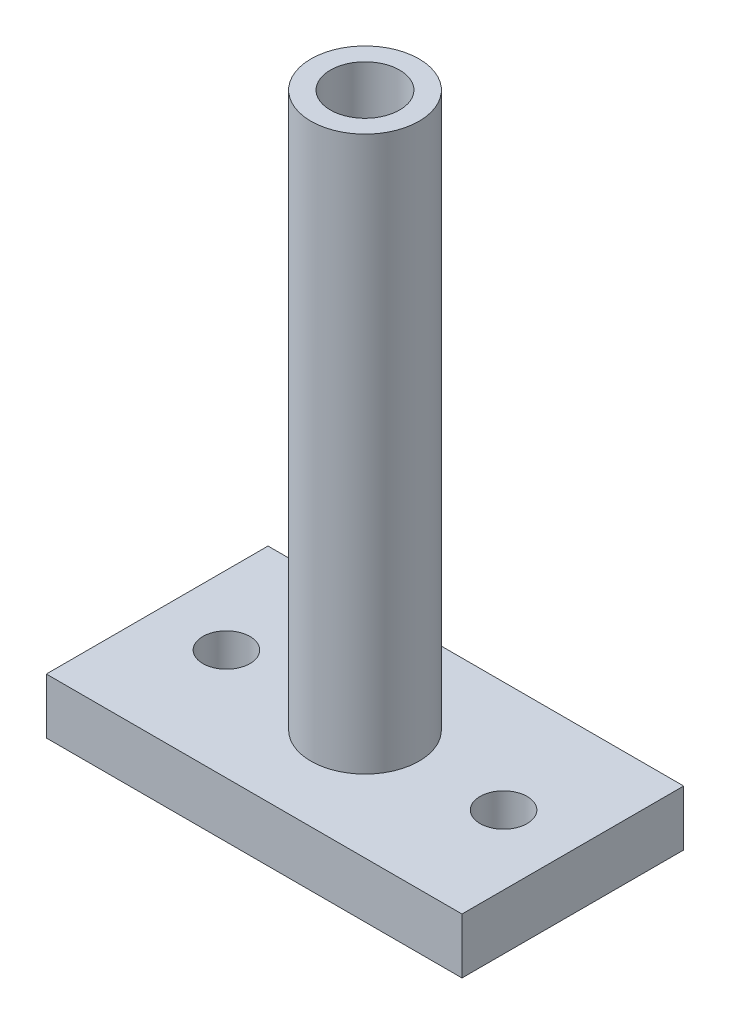
SolidWorks part; units mm, degrees
ref_plane "前视基准面" through (0, 0, 0) normal (0, 0, 1) x (1, 0, 0)
ref_plane "上视基准面" through (0, 0, 0) normal (0, 1, 0) x (1, 0, 0)
ref_plane "右视基准面" through (0, 0, 0) normal (1, 0, 0) x (0, 0, -1)
other "Configuration Table"
sketch "草图1" plane through (0, 0, 0) normal (0, 1, 0) x (1, 0, 0)
  line L0 (7.5, 0) -> (7.5, 8) construction
  line L1 (0, 0) -> (15, 0)
  line L2 (0, 0) -> (0, 8)
  line L3 (0, 8) -> (15, 8)
  line L4 (15, 0) -> (15, 8)
  line L5 (0, 4) -> (15, 4) construction
  circle A0 centre (2.5, 4) radius 0.85
  circle A1 centre (12.5, 4) radius 0.85
  dimension "D3" = 1.7
  dimension "D1" = 15
  dimension "D2" = 8
  dimension "D4" = 5
extrude "凸台-拉伸1" add sketch "草图1" along normal blind 2
sketch "草图2" plane through (0, 2, 0) normal (0, 1, 0) x (1, 0, 0)
  line L0 (7.5, 0) -> (7.5, 8) construction
  line L1 (0, 0) -> (15, 0) construction
  line L2 (15, 8) -> (0, 8) construction
  circle A0 centre (7.5, 4) radius 1.95
  dimension "D1" = 3.9
extrude "凸台-拉伸2" add sketch "草图2" along normal blind 20
sketch "草图3" plane through (0, 22, 0) normal (0, 1, 0) x (1, 0, 0)
  circle A0 centre (7.5, 4) radius 1.25
  dimension "D1" = 2.5
extrude "切除-拉伸1" cut sketch "草图3" against normal blind 10
